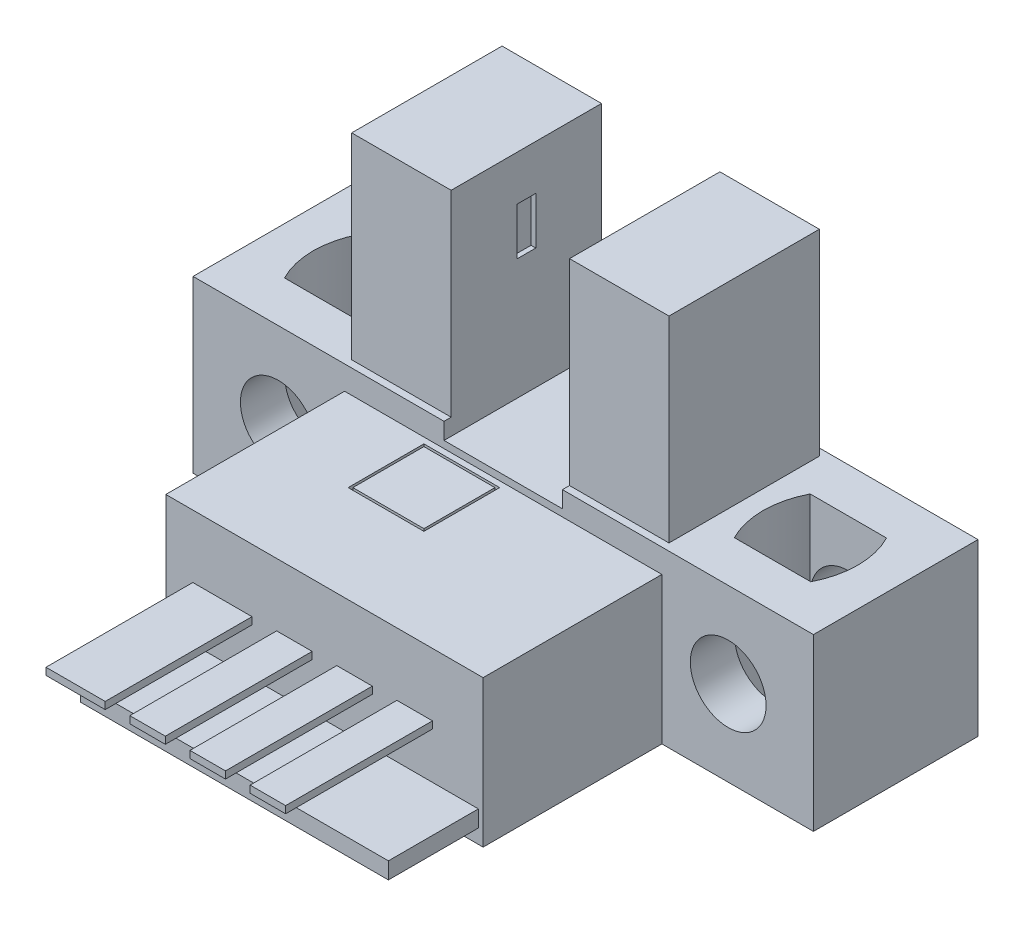
SolidWorks part; units mm, degrees
ref_plane "Front Plane" through (0, 0, 0) normal (0, 0, 1) x (1, 0, 0)
ref_plane "Top Plane" through (0, 0, 0) normal (0, 1, 0) x (1, 0, 0)
ref_plane "Right Plane" through (0, 0, 0) normal (1, 0, 0) x (0, 0, -1)
ref_plane "Plane1" through (0, 0, 6.95) normal (0, 0, 1) x (1, 0, 0)
sketch "Sketch1" plane through (0, 0, 6.95) normal (0, 0, 1) x (1, 0, 0)
  line L0 (22.6, 3.6) -> (-3.6, 3.6)
  line L1 (-3.6, 3.6) -> (-3.6, -3.6)
  line L2 (-3.6, -3.6) -> (22.6, -3.6)
  line L3 (22.6, -3.6) -> (22.6, 3.6)
extrude "Boss-Extrude1" add sketch "Sketch1" against normal blind 6.95
sketch "Sketch2" plane through (0, 0, 0) normal (0, 0, -1) x (-1, 0, 0)
  line L0 (-7, 3.6) -> (-12, 3.6)
  line L1 (-12, 3.6) -> (-12, 2.9)
  line L2 (-12, 2.9) -> (-7, 2.9)
  line L3 (-7, 2.9) -> (-7, 3.6)
extrude "Cut-Extrude1" cut sketch "Sketch2" against normal through all
sketch "Sketch3" plane through (0, -3.6, 0) normal (0, -1, 0) x (1, 0, 0)
  line L0 (1.6129, 5.075) -> (-1.6129, 5.075)
  line L1 (-1.6129, 1.875) -> (1.6129, 1.875)
  arc A0 (-1.6129, 5.075) -> (-1.6129, 1.875) centre (1.5, 3.475) ccw
  arc A1 (1.6129, 1.875) -> (1.6129, 5.075) centre (-1.5, 3.475) ccw
extrude "Cut-Extrude2" cut sketch "Sketch3" against normal through all
sketch "Sketch4" plane through (0, -3.6, 0) normal (0, -1, 0) x (1, 0, 0)
  line L0 (17.3871, 1.875) -> (20.6129, 1.875)
  line L1 (20.6129, 5.075) -> (17.3871, 5.075)
  arc A0 (20.6129, 1.875) -> (20.6129, 5.075) centre (17.5, 3.475) ccw
  arc A1 (17.3871, 5.075) -> (17.3871, 1.875) centre (20.5, 3.475) ccw
extrude "Cut-Extrude3" cut sketch "Sketch4" against normal through all
sketch "Sketch5" plane through (0, 0, 6.95) normal (0, 0, 1) x (1, 0, 0)
  line L0 (2.8, 2.6) -> (16.2, 2.6)
  line L1 (16.2, 2.6) -> (16.2, -3.6)
  line L2 (16.2, -3.6) -> (2.8, -3.6)
  line L3 (2.8, -3.6) -> (2.8, 2.6)
extrude "Boss-Extrude2" add sketch "Sketch5" along normal blind 7.55
sketch "Sketch6" plane through (0, 0, 14.5) normal (0, 0, 1) x (1, 0, 0)
  line L0 (3, -2.3) -> (16, -2.3)
  line L1 (16, -2.3) -> (16, -3)
  line L2 (16, -3) -> (3, -3)
  line L3 (3, -3) -> (3, -2.3)
extrude "Boss-Extrude3" add sketch "Sketch6" along normal blind 3.8
sketch "Sketch7" plane through (0, 0, 14.5) normal (0, 0, 1) x (1, 0, 0)
  line L0 (12.56, -0.05) -> (14.06, -0.05)
  line L1 (14.06, -0.05) -> (14.06, -0.35)
  line L2 (14.06, -0.35) -> (12.56, -0.35)
  line L3 (12.56, -0.35) -> (12.56, -0.05)
extrude "Boss-Extrude4" add sketch "Sketch7" along normal blind 6.2
sketch "Sketch8" plane through (0, 0, 14.5) normal (0, 0, 1) x (1, 0, 0)
  line L0 (10.02, -0.05) -> (11.52, -0.05)
  line L1 (11.52, -0.05) -> (11.52, -0.35)
  line L2 (11.52, -0.35) -> (10.02, -0.35)
  line L3 (10.02, -0.35) -> (10.02, -0.05)
extrude "Boss-Extrude5" add sketch "Sketch8" along normal blind 6.2
sketch "Sketch9" plane through (0, 0, 14.5) normal (0, 0, 1) x (1, 0, 0)
  line L0 (8.98, -0.05) -> (8.98, -0.35)
  line L1 (8.98, -0.35) -> (7.48, -0.35)
  line L2 (7.48, -0.35) -> (7.48, -0.05)
  line L3 (7.48, -0.05) -> (8.98, -0.05)
extrude "Boss-Extrude6" add sketch "Sketch9" along normal blind 6.2
sketch "Sketch10" plane through (0, 0, 14.5) normal (0, 0, 1) x (1, 0, 0)
  line L0 (3.94, -0.05) -> (6.44, -0.05)
  line L1 (6.44, -0.05) -> (6.44, -0.35)
  line L2 (6.44, -0.35) -> (3.94, -0.35)
  line L3 (3.94, -0.35) -> (3.94, -0.05)
extrude "Boss-Extrude7" add sketch "Sketch10" along normal blind 6.2
sketch "Sketch11" plane through (0, 2.6, 0) normal (0, 1, 0) x (-1, 0, 0)
  line L0 (-9.6, 7.2) -> (-6.4, 7.2)
  line L1 (-6.4, 7.2) -> (-6.4, 10.4)
  line L2 (-6.4, 10.4) -> (-9.6, 10.4)
  line L3 (-9.6, 10.4) -> (-9.6, 7.2)
extrude "Cut-Extrude4" cut sketch "Sketch11" against normal blind 1
sketch "Sketch12" plane through (0, 1.6, 0) normal (0, 1, 0) x (-1, 0, 0)
  line L0 (-6.5, 7.3) -> (-9.5, 7.3)
  line L1 (-9.5, 7.3) -> (-9.5, 10.3)
  line L2 (-9.5, 10.3) -> (-6.5, 10.3)
  line L3 (-6.5, 10.3) -> (-6.5, 7.3)
extrude "Boss-Extrude8" add sketch "Sketch12" along normal blind 1
sketch "Sketch13" plane through (0, 3.6, 0) normal (0, 1, 0) x (-1, 0, 0)
  line L0 (-12, 6.65) -> (-12, 0.3)
  line L1 (-12, 0.3) -> (-16.2, 0.3)
  line L2 (-16.2, 0.3) -> (-16.2, 6.65)
  line L3 (-16.2, 6.65) -> (-12, 6.65)
extrude "Boss-Extrude9" add sketch "Sketch13" along normal blind 8.3
sketch "Sketch14" plane through (12, 0, 0) normal (-1, 0, 0) x (0, 0, 1)
  line L0 (3.875, 10) -> (3.075, 10)
  line L1 (3.075, 10) -> (3.075, 8)
  line L2 (3.075, 8) -> (3.875, 8)
  line L3 (3.875, 8) -> (3.875, 10)
extrude "Cut-Extrude5" cut sketch "Sketch14" against normal blind 0.2
sketch "Sketch15" plane through (0, 3.6, 0) normal (0, 1, 0) x (-1, 0, 0)
  line L0 (-7, 0.3) -> (-7, 6.65)
  line L1 (-7, 6.65) -> (-2.8, 6.65)
  line L2 (-2.8, 6.65) -> (-2.8, 0.3)
  line L3 (-2.8, 0.3) -> (-7, 0.3)
extrude "Boss-Extrude10" add sketch "Sketch15" along normal blind 8.3
sketch "Sketch16" plane through (7, 0, 0) normal (1, 0, 0) x (0, 0, -1)
  line L0 (-3.875, 8) -> (-3.075, 8)
  line L1 (-3.075, 8) -> (-3.075, 10)
  line L2 (-3.075, 10) -> (-3.875, 10)
  line L3 (-3.875, 10) -> (-3.875, 8)
extrude "Cut-Extrude6" cut sketch "Sketch16" against normal blind 0.2
hole_wizard "Ø3.2 (3.2) Diameter Hole1" positions "Sketch18" profile "Sketch17" hole size "Ø3.2" standard "ANSI Metric"
sketch "Sketch18" plane through (0, 0, 0) normal (0, 0, -1) x (-1, 0, 0)
  point P0 (0, 0)
  point P1 (-19, 0)
sketch "Sketch17" plane through (0, 0, 0) normal (1, 0, 0) x (0, 1, 0)
  line L0 (0, 0) -> (0, 1.875)
  line L1 (0, 1.875) -> (1.6, 1.875)
  line L2 (1.6, 1.875) -> (1.6, 0)
  line L5 (1.6, 0) -> (0, 0)
  line L11 (0, -6.35) -> (0, 107.95) construction
  dimension "Thru Hole Dia." = 3.2
  dimension "Thru Hole Depth" = 1.875
hole_wizard "Ø3.2 (3.2) Diameter Hole2" positions "Sketch20" profile "Sketch19" hole size "Ø3.2" standard "ANSI Metric"
sketch "Sketch20" plane through (0, 0, 6.95) normal (0, 0, 1) x (1, 0, 0)
  point P0 (19, 0)
  point P1 (0, 0)
sketch "Sketch19" plane through (19, 0, 6.95) normal (1, 0, 0) x (0, -1, 0)
  line L0 (0, 0) -> (0, 6.95)
  line L1 (0, 6.95) -> (1.6, 6.95)
  line L2 (1.6, 6.95) -> (1.6, 0)
  line L5 (1.6, 0) -> (0, 0)
  line L11 (0, -6.35) -> (0, 107.95) construction
  dimension "Thru Hole Dia." = 3.2
  dimension "Thru Hole Depth" = 6.95
sketch "Sketch21" plane through (0, 0, 0) normal (0, 0, -1) x (-1, 0, 0)
  point P0 (0, 0)
  point P1 (-19, 0)
